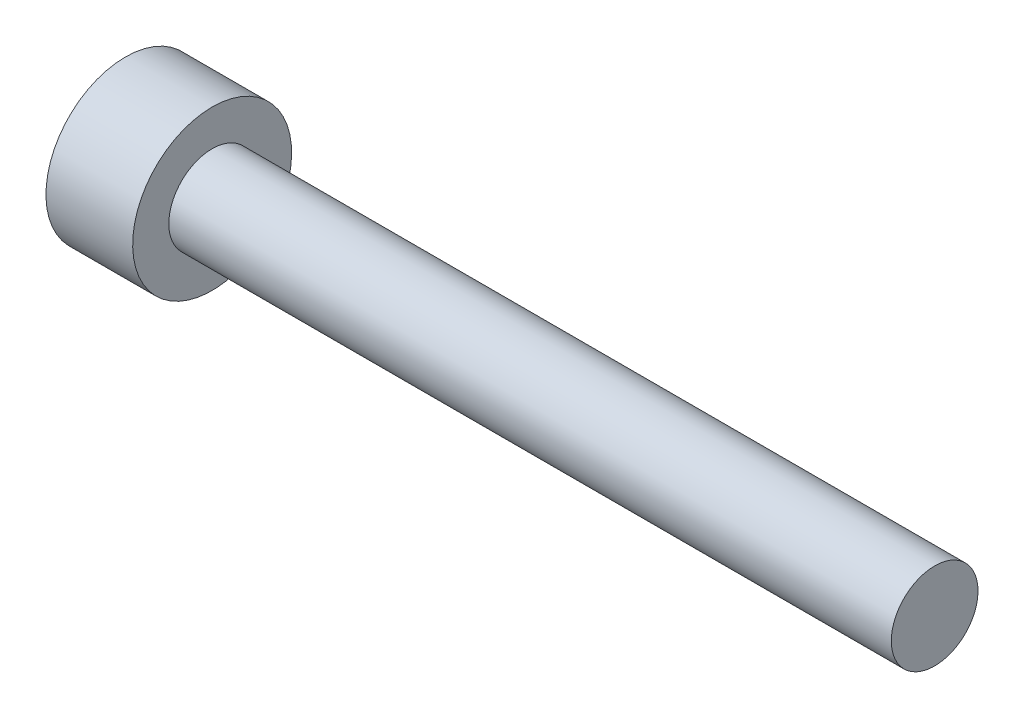
SolidWorks part; units mm, degrees
material "1.0721 (10S20)"
ref_plane "Płaszczyzna przednia" through (0, 0, 0) normal (0, 0, 1) x (1, 0, 0)
ref_plane "Płaszczyzna górna" through (0, 0, 0) normal (0, 1, 0) x (1, 0, 0)
ref_plane "Płaszczyzna prawa" through (0, 0, 0) normal (1, 0, 0) x (0, 0, -1)
sketch "Sketch1" plane through (0, 0, 0) normal (0, 0, 1) x (1, 0, 0)
  line L0 (0, 0) -> (0, 2.75)
  line L1 (0, 2.75) -> (3, 2.75)
  line L2 (3, 2.75) -> (3, 1.5)
  line L3 (3, 1.5) -> (28, 1.5)
  line L4 (28, 1.5) -> (28, 0)
  line L5 (28, 0) -> (0, 0)
  dimension "D1" = 25
  dimension "D2" = 3
  dimension "D3" = 2.75
  dimension "D4" = 1.5
revolve "Revolve1" add sketch "Sketch1" angle 360 about L5
sketch "Sketch2" plane through (0, 0, 0) normal (-1, 0, 0) x (0, 0, 1)
  line L1 (0, 1.4722) -> (-1.275, 0.7361)
  line L2 (-1.275, 0.7361) -> (-1.275, -0.7361)
  line L3 (-1.275, -0.7361) -> (0, -1.4722)
  line L4 (0, -1.4722) -> (1.275, -0.7361)
  line L5 (1.275, -0.7361) -> (1.275, 0.7361)
  line L6 (1.275, 0.7361) -> (0, 1.4722)
  circle A0 centre (0, 0) radius 1.275 construction
  dimension "D1" = 2.55
extrude "Cut-Extrude1" cut sketch "Sketch2" against normal blind 1.3
